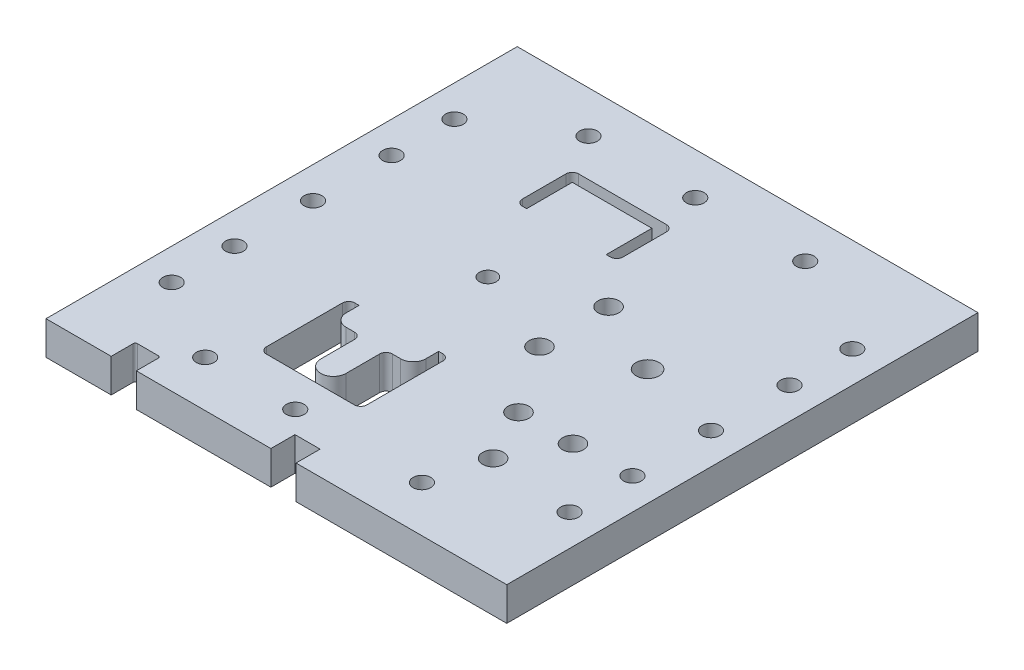
SolidWorks part; units mm, degrees
material "Plain Carbon Steel"
ref_plane "Front Plane" through (0, 0, 0) normal (0, 0, 1) x (1, 0, 0)
ref_plane "Top Plane" through (0, 0, 0) normal (0, 1, 0) x (1, 0, 0)
ref_plane "Right Plane" through (0, 0, 0) normal (1, 0, 0) x (0, 0, -1)
sketch "Sketch1" plane through (0, 0, 0) normal (0, 1, 0) x (1, 0, 0)
  line L1 (-110, -112.5) -> (110, -112.5)
  line L2 (-110, -112.5) -> (-110, 112.5)
  line L3 (-110, 112.5) -> (110, 112.5)
  line L4 (110, -112.5) -> (110, 112.5)
  line L5 (-110, -112.5) -> (110, 112.5) construction
  line L6 (-110, 112.5) -> (110, -112.5) construction
  point P0 (0, 0)
  dimension "D1" = 225
  dimension "D2" = 220
extrude "Boss-Extrude1" add sketch "Sketch1" against normal blind 16
sketch "Sketch2" plane through (0, 0, 0) normal (0, 1, 0) x (1, 0, 0)
  line L0 (-21.75, 69.53) -> (-21.75, -69.53) construction
  circle A0 centre (-21.75, 10.23) radius 4
  circle A4 centre (-21.75, 10.23) radius 5 construction
  dimension "D1" = 8
extrude "Cut-Extrude1" cut sketch "Sketch2" against normal up to next
sketch "Sketch3" plane through (0, -16, 0) normal (0, -1, 0) x (1, 0, 0)
  line L0 (-68.37, 102) -> (-77.37, 102) construction
  line L78 (-72.87, 102) -> (-72.87, 112.5) construction
  line L79 (-110, 112.5) -> (110, 112.5) construction
  line L80 (3.38, 102) -> (3.38, 112.5) construction
  line L81 (7.88, 102) -> (-1.12, 102) construction
  line L82 (-1.62, 102.5) -> (-1.62, 115) construction
  line L83 (-77.87, 101) -> (-67.87, 101)
  line L84 (-78.87, 102) -> (-78.87, 112.5)
  line L85 (-78.87, 112.5) -> (-66.87, 112.5)
  line L86 (-66.87, 102) -> (-66.87, 112.5)
  line L87 (-2.62, 101) -> (9.38, 101)
  line L88 (-2.62, 101) -> (-2.62, 112.5)
  line L89 (-2.62, 112.5) -> (9.38, 112.5)
  line L90 (9.38, 101) -> (9.38, 112.5)
  line L91 (8.38, 115) -> (8.38, 102.5) construction
  line L92 (-67.87, 115) -> (-67.87, 102.5) construction
  line L93 (-77.87, 102.5) -> (-77.87, 115) construction
  arc A0 (-67.87, 101) -> (-66.87, 102) centre (-67.87, 102) ccw
  arc A1 (-77.87, 101) -> (-78.87, 102) centre (-77.87, 102) cw
  dimension "D7" = 1
  dimension "D1" = 1
  dimension "D2" = 1
  dimension "D3" = 1
  dimension "D4" = 1
  dimension "D5" = 1
  dimension "D6" = 1
extrude "Cut-Extrude2" cut sketch "Sketch3" against normal up to next
sketch "Sketch4" plane through (0, -16, 0) normal (0, -1, 0) x (1, 0, 0)
  circle A0 centre (-35, 100) radius 8.5
  circle A1 centre (25, 100) radius 8.5
  circle A2 centre (70, 100) radius 8.5
  circle A3 centre (-35, -100) radius 8.5
  circle A4 centre (25, -100) radius 8.5
  circle A5 centre (70, -100) radius 8.5
  dimension "D1" = 17
extrude "Cut-Extrude3" cut sketch "Sketch4" against normal blind 5
hole_wizard "M10 Tapped Hole2" positions "Sketch27" profile "Sketch9" tap size "M10" standard "ISO" end condition through all
sketch "Sketch27" plane through (0, 0, 0) normal (0, 1, 0) x (1, 0, 0)
  line L1 (110, 112.5) -> (-110, 112.5) construction
  line L2 (-110, 112.5) -> (-110, -112.5) construction
  line L3 (0, 112.5) -> (0, -112.5) construction
  line L5 (-66.87, -112.5) -> (-2.62, -112.5) construction
  line L6 (-110, -112.5) -> (-78.87, -112.5) construction
  circle A0 centre (-95, 67.5) radius 12.5 construction
  circle A1 centre (-95, 37.5) radius 12.5 construction
  circle A2 centre (-95, -67.5) radius 12.5 construction
  circle A3 centre (95, -37.5) radius 12.5 construction
  point P0 (-95, -67.5)
  point P2 (-95, -37.5)
  point P4 (-95, 0)
  point P6 (-95, 37.5)
  point P8 (-95, 67.5)
  point P28 (95, 67.5)
  point P29 (95, 37.5)
  point P30 (95, 0)
  point P31 (95, -37.5)
  point P32 (95, -67.5)
  dimension "D1" = 25
  dimension "D2" = 45
  dimension "D3" = 30
  dimension "D4" = 37.5
  dimension "D5" = 37.5
  dimension "D6" = 45
  dimension "D7" = 15
sketch "Sketch9" plane through (-95, 0, 67.5) normal (1, 0, 0) x (0, 0, 1)
  line L0 (0, 0) -> (0, 16)
  line L1 (0, 16) -> (4.25, 16)
  line L2 (4.25, 16) -> (4.25, 0)
  line L5 (4.25, 0) -> (0, 0)
  line L11 (0, -6.35) -> (0, 107.95) construction
  dimension "Thru Tap Drill Dia." = 8.5
  dimension "Thru Tap Drill Depth" = 16
cosmetic thread "Hole Thread23" parameters "D2"=10
cosmetic thread "Hole Thread24" parameters "D2"=10
cosmetic thread "Hole Thread25" parameters "D2"=10
cosmetic thread "Hole Thread26" parameters "D2"=10
cosmetic thread "Hole Thread27" parameters "D2"=10
cosmetic thread "Hole Thread28" parameters "D2"=10
cosmetic thread "Hole Thread29" parameters "D2"=10
cosmetic thread "Hole Thread30" parameters "D2"=10
cosmetic thread "Hole Thread31" parameters "D2"=10
cosmetic thread "Hole Thread32" parameters "D2"=10
hole_wizard "M10 Tapped Hole3" positions "Sketch18" profile "Sketch15" tap size "M10" standard "ISO" end condition through all
sketch "Sketch18" plane through (0, 0, 0) normal (0, 1, 0) x (1, 0, 0)
  line L0 (-110, 112.5) -> (-110, -112.5) construction
  line L1 (110, 112.5) -> (-110, 112.5) construction
  circle A0 centre (-56, 92.5) radius 12.5 construction
  circle A1 centre (-95, 67.5) radius 12.5 construction
  circle A2 centre (95, 67.5) radius 12.5 construction
  circle A4 centre (47.5, 92.5) radius 12.5 construction
  circle A5 centre (-5, 92.5) radius 12.5 construction
  point P0 (-56, 92.5)
  point P2 (-5, 92.5)
  point P4 (47.5, 92.5)
  dimension "D1" = 25
  dimension "D2" = 54
  dimension "D3" = 51
  dimension "D4" = 52.5
  dimension "D6" = 20
sketch "Sketch15" plane through (-56, 0, -92.5) normal (1, 0, 0) x (0, 0, 1)
  line L0 (0, 0) -> (0, 16)
  line L1 (0, 16) -> (4.25, 16)
  line L2 (4.25, 16) -> (4.25, 0)
  line L5 (4.25, 0) -> (0, 0)
  line L11 (0, -6.35) -> (0, 107.95) construction
  dimension "Thru Tap Drill Dia." = 8.5
  dimension "Thru Tap Drill Depth" = 16
cosmetic thread "Hole Thread34" parameters "D2"=10
cosmetic thread "Hole Thread35" parameters "D2"=10
cosmetic thread "Hole Thread36" parameters "D2"=10
sketch "Sketch20" plane through (0, 0, 0) normal (0, 1, 0) x (1, 0, 0)
  line L5 (110, 112.5) -> (-110, 112.5) construction
  line L6 (110, -112.5) -> (110, 112.5) construction
  line L7 (-110, 112.5) -> (-110, -112.5) construction
  line L8 (9.38, -112.5) -> (110, -112.5) construction
  circle A2 centre (-13, -90.5) radius 12.5 construction
  circle A5 centre (55, -15.5) radius 12.5 construction
  circle A6 centre (47.5, -90.5) radius 12.5 construction
  circle A7 centre (-53, 32.5) radius 12.5 construction
  circle A8 centre (-53, -17.5) radius 12.5 construction
  circle A10 centre (55, 61) radius 12.5 construction
  circle A12 centre (3, 10.5) radius 12.5 construction
  circle A14 centre (-56, 92.5) radius 12.5 construction
  circle A15 centre (-5, 92.5) radius 12.5 construction
  circle A16 centre (47.5, 92.5) radius 12.5 construction
  circle A17 centre (-56, -90.5) radius 12.5 construction
  dimension "D8" = 25
  dimension "D13" = 80
  dimension "D2" = 55
  dimension "D3" = 57
  dimension "D4" = 102
  dimension "D5" = 113
  dimension "D6" = 128
  dimension "D7" = 22
  dimension "D9" = 97
  dimension "D10" = 62.5
  dimension "D11" = 50
  dimension "D12" = 51.5
  dimension "D14" = 54
hole_wizard "M10 Tapped Hole4" positions "Sketch30" profile "Sketch22" tap size "M10" standard "ISO" end condition through all
sketch "Sketch30" plane through (0, 0, 0) normal (0, 1, 0) x (1, 0, 0)
  point P15 (-13, -90.5)
  point P18 (47.5, -90.5)
  point P22 (-56, -90.5)
sketch "Sketch22" plane through (-13, 0, 90.5) normal (1, 0, 0) x (0, 0, 1)
  line L0 (0, 0) -> (0, 16)
  line L1 (0, 16) -> (4.25, 16)
  line L2 (4.25, 16) -> (4.25, 0)
  line L5 (4.25, 0) -> (0, 0)
  line L11 (0, -6.35) -> (0, 107.95) construction
  dimension "Thru Tap Drill Dia." = 8.5
  dimension "Thru Tap Drill Depth" = 16
cosmetic thread "Hole Thread41" parameters "D2"=10
cosmetic thread "Hole Thread49" parameters "D2"=10
cosmetic thread "Hole Thread50" parameters "D2"=10
sketch "Sketch24" plane through (0, 0, 0) normal (0, 1, 0) x (1, 0, 0)
  line L22 (2.25, -35.27) -> (2.25, -71.53) construction
  line L27 (-45.75, -71.53) -> (-45.75, -35.27) construction
  line L28 (2.25, -35.27) -> (2.25, -71.53)
  line L29 (-45.75, -71.53) -> (-45.75, -35.27)
  line L30 (-42.75, -32.27) -> (-40.75, -32.27)
  line L31 (-2.75, -32.27) -> (-0.75, -32.27)
  line L32 (-42.75, -74.53) -> (-0.75, -74.53)
  line L37 (15.25, -32.27) -> (-2.75, -32.27)
  line L38 (-2.75, -32.27) -> (-2.75, -38.4)
  line L39 (-8.75, -44.4) -> (-12.75, -44.4)
  line L40 (-15.75, -47.4) -> (-15.75, -63.53)
  line L41 (-27.75, -63.53) -> (-27.75, -47.4)
  line L42 (-30.75, -44.4) -> (-34.75, -44.4)
  line L43 (-40.75, -38.4) -> (-40.75, -32.27)
  line L44 (-40.75, -32.27) -> (-58.75, -32.27)
  line L45 (-61.75, -35.27) -> (-61.75, -71.53)
  line L46 (-58.75, -74.53) -> (15.25, -74.53)
  line L47 (18.25, -71.53) -> (18.25, -35.27)
  line L49 (-2.75, -32.27) -> (-2.75, -38.4)
  line L50 (-8.75, -44.4) -> (-12.75, -44.4)
  line L51 (-15.75, -47.4) -> (-15.75, -63.53)
  line L52 (-27.75, -63.53) -> (-27.75, -47.4)
  line L53 (-30.75, -44.4) -> (-34.75, -44.4)
  line L54 (-40.75, -38.4) -> (-40.75, -32.27)
  arc A20 (2.25, -35.27) -> (-0.75, -32.27) centre (-0.75, -35.27) ccw construction
  arc A21 (-0.75, -74.53) -> (2.25, -71.53) centre (-0.75, -71.53) ccw construction
  arc A22 (-45.75, -71.53) -> (-42.75, -74.53) centre (-42.75, -71.53) ccw construction
  arc A23 (-42.75, -32.27) -> (-45.75, -35.27) centre (-42.75, -35.27) ccw construction
  arc A24 (2.25, -35.27) -> (-0.75, -32.27) centre (-0.75, -35.27) ccw
  arc A25 (-0.75, -74.53) -> (2.25, -71.53) centre (-0.75, -71.53) ccw
  arc A26 (-45.75, -71.53) -> (-42.75, -74.53) centre (-42.75, -71.53) ccw
  arc A27 (-42.75, -32.27) -> (-45.75, -35.27) centre (-42.75, -35.27) ccw
  arc A29 (-8.75, -44.4) -> (-2.75, -38.4) centre (-8.75, -38.4) ccw
  arc A30 (-12.75, -44.4) -> (-15.75, -47.4) centre (-12.75, -47.4) ccw
  arc A31 (-27.75, -63.53) -> (-15.75, -63.53) centre (-21.75, -63.53) ccw
  arc A32 (-27.75, -47.4) -> (-30.75, -44.4) centre (-30.75, -47.4) ccw
  arc A33 (-40.75, -38.4) -> (-34.75, -44.4) centre (-34.75, -38.4) ccw
  arc A34 (-58.75, -32.27) -> (-61.75, -35.27) centre (-58.75, -35.27) ccw
  arc A35 (-61.75, -71.53) -> (-58.75, -74.53) centre (-58.75, -71.53) ccw
  arc A36 (15.25, -74.53) -> (18.25, -71.53) centre (15.25, -71.53) ccw
  arc A37 (18.25, -35.27) -> (15.25, -32.27) centre (15.25, -35.27) ccw
  arc A38 (-8.75, -44.4) -> (-2.75, -38.4) centre (-8.75, -38.4) ccw
  arc A39 (-12.75, -44.4) -> (-15.75, -47.4) centre (-12.75, -47.4) ccw
  arc A40 (-27.75, -63.53) -> (-15.75, -63.53) centre (-21.75, -63.53) ccw
  arc A41 (-27.75, -47.4) -> (-30.75, -44.4) centre (-30.75, -47.4) ccw
  arc A42 (-40.75, -38.4) -> (-34.75, -44.4) centre (-34.75, -38.4) ccw
  dimension "D1" = 0
extrude "Cut-Extrude4" cut sketch "Sketch24" against normal up to next
sketch "Sketch29" plane through (0, -16, 0) normal (0, -1, 0) x (1, 0, 0)
  line L0 (-2.75, -47.73) -> (-0.75, -47.73) construction
  line L1 (-2.75, -16.73) -> (-2.75, -69.53) construction
  line L2 (2.25, -50.73) -> (2.25, -71.53) construction
  line L3 (-0.75, -74.53) -> (-42.75, -74.53) construction
  line L4 (-2.75, -69.53) -> (-40.75, -69.53) construction
  line L5 (-40.75, -69.53) -> (-40.75, -34.23) construction
  line L6 (-42.75, -47.73) -> (-40.75, -47.73) construction
  line L7 (-45.75, -71.53) -> (-45.75, -50.73) construction
  line L8 (-2.75, -47.73) -> (-0.75, -47.73)
  line L9 (-2.75, -47.73) -> (-2.75, -69.53)
  line L10 (2.25, -50.73) -> (2.25, -71.53)
  line L11 (-0.75, -74.53) -> (-42.75, -74.53)
  line L12 (-2.75, -69.53) -> (-40.75, -69.53)
  line L13 (-40.75, -69.53) -> (-40.75, -47.73)
  line L14 (-42.75, -47.73) -> (-40.75, -47.73)
  line L15 (-45.75, -71.53) -> (-45.75, -50.73)
  arc A0 (2.25, -50.73) -> (-0.75, -47.73) centre (-0.75, -50.73) ccw construction
  arc A1 (-0.75, -74.53) -> (2.25, -71.53) centre (-0.75, -71.53) ccw construction
  arc A2 (-45.75, -71.53) -> (-42.75, -74.53) centre (-42.75, -71.53) ccw construction
  arc A3 (-42.75, -47.73) -> (-45.75, -50.73) centre (-42.75, -50.73) ccw construction
  arc A4 (2.25, -50.73) -> (-0.75, -47.73) centre (-0.75, -50.73) ccw
  arc A5 (-0.75, -74.53) -> (2.25, -71.53) centre (-0.75, -71.53) ccw
  arc A6 (-45.75, -71.53) -> (-42.75, -74.53) centre (-42.75, -71.53) ccw
  arc A7 (-42.75, -47.73) -> (-45.75, -50.73) centre (-42.75, -50.73) ccw
extrude "Cut-Extrude6" cut sketch "Sketch29" against normal up to next
hole_wizard "Ø10.0mm Dowel Hole1" positions "Sketch33" profile "Sketch32" hole size "Ø10.0" standard "ISO" end condition through all
sketch "Sketch33" plane through (0, 0, 0) normal (0, 1, 0) x (1, 0, 0)
  point P0 (54.5, -63.53)
  point P3 (67.5, -38.4)
  point P6 (41.5, -38.4)
  point P9 (19.38, 26.73)
  point P12 (19.38, -6.27)
sketch "Sketch32" plane through (54.5, 0, 63.53) normal (1, 0, 0) x (0, 0, 1)
  line L0 (0, 0) -> (0, 16)
  line L1 (0, 16) -> (5, 16)
  line L2 (5, 16) -> (5, 0)
  line L5 (5, 0) -> (0, 0)
  line L11 (0, -6.35) -> (0, 107.95) construction
  dimension "Thru Hole Dia." = 10
  dimension "Thru Hole Depth" = 16
sketch "Sketch34" plane through (0, 0, 0) normal (0, 1, 0) x (1, 0, 0)
  circle A0 centre (54.5, 10.23) radius 5 construction
  circle A1 centre (54.5, 10.23) radius 5
extrude "Cut-Extrude7" cut sketch "Sketch34" against normal up to next
ref_point "Point2"
ref_plane "Plane1" through (0, 0, -10.23) normal (0, 0, 1) x (1, 0, 0)
sketch "Sketch35" plane through (0, 0, -10.23) normal (0, 0, 1) x (1, 0, 0)
  line L0 (59.5, -10) -> (60.0241, 0)
  line L1 (59.5, -16) -> (59.5, 0) construction
  line L2 (9.38, 0) -> (110, 0) construction
  line L3 (60.0241, 0) -> (59.5, 0)
  line L4 (59.5, 0) -> (59.5, -10)
  line L5 (9.38, -16) -> (110, -16) construction
  dimension "D1" = 6
  dimension "D2" = 3
sweep "Cut-Sweep1" cut profiles "Sketch35" path edge at (54.5, 0, -5.23)
